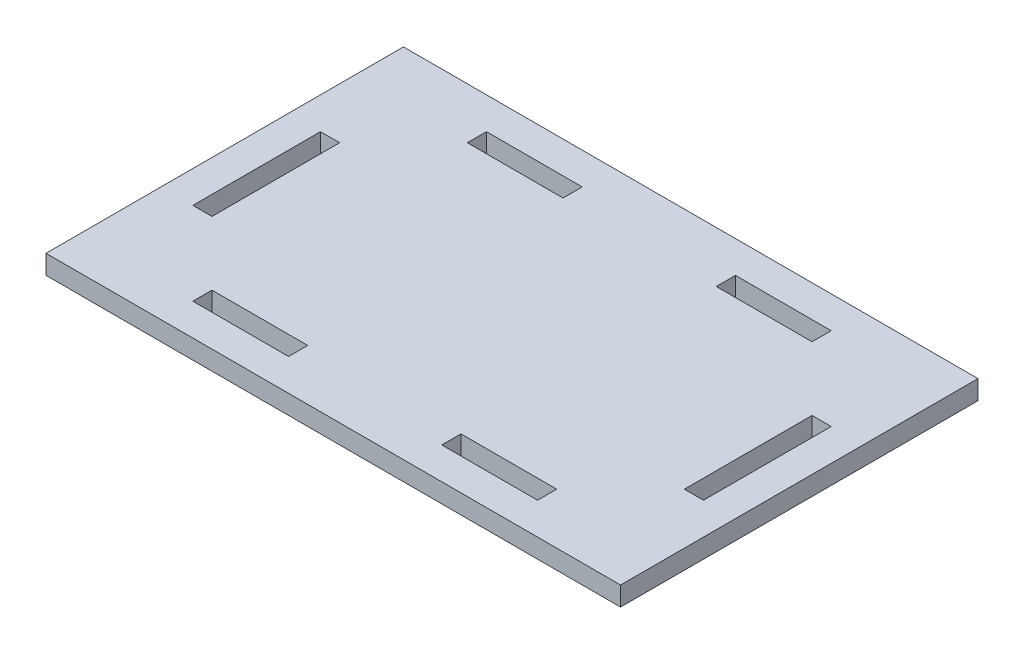
SolidWorks part; units mm, degrees
ref_plane "前视基准面" through (0, 0, 0) normal (0, 0, 1) x (1, 0, 0)
ref_plane "上视基准面" through (0, 0, 0) normal (0, 1, 0) x (1, 0, 0)
ref_plane "右视基准面" through (0, 0, 0) normal (1, 0, 0) x (0, 0, -1)
other "Configuration Table"
sketch "草图1" plane through (0, 0, 0) normal (0, 1, 0) x (1, 0, 0)
  line L0 (0, 12.4054) -> (0, -7.9459) construction
  line L1 (-45, 28) -> (45, 28)
  line L2 (-45, 28) -> (-45, -28)
  line L3 (-45, -28) -> (45, -28)
  line L4 (45, 28) -> (45, -28)
  line L5 (-45, 28) -> (45, -28) construction
  line L6 (-45, -28) -> (45, 28) construction
  line L7 (-40, 10) -> (-37, 10)
  line L8 (-40, 10) -> (-40, -10)
  line L9 (-40, -10) -> (-37, -10)
  line L10 (-37, 10) -> (-37, -10)
  line L11 (40, -10) -> (37, -10)
  line L12 (37, 10) -> (37, -10)
  line L13 (40, 10) -> (37, 10)
  line L14 (40, 10) -> (40, -10)
  line L15 (27, 20) -> (12, 20)
  line L16 (-27, 23) -> (-12, 23)
  line L17 (-27, 23) -> (-27, 20)
  line L18 (-27, 20) -> (-12, 20)
  line L19 (-12, 23) -> (-12, 20)
  line L20 (12, 23) -> (12, 20)
  line L21 (27, 23) -> (12, 23)
  line L22 (27, 23) -> (27, 20)
  line L23 (-10.6216, 0) -> (9.2432, 0) construction
  line L24 (27, -23) -> (27, -20)
  line L25 (27, -23) -> (12, -23)
  line L26 (12, -23) -> (12, -20)
  line L27 (27, -20) -> (12, -20)
  line L28 (-27, -20) -> (-12, -20)
  line L29 (-12, -23) -> (-12, -20)
  line L30 (-27, -23) -> (-12, -23)
  line L31 (-27, -23) -> (-27, -20)
  point P0 (0, 0)
  point P10 (-37, 0)
  dimension "D1" = 90
  dimension "D2" = 56
  dimension "D3" = 3
  dimension "D4" = 20
  dimension "D5" = 5
  dimension "D6" = 15
  dimension "D7" = 5
  dimension "D8" = 12
extrude "凸台-拉伸1" add sketch "草图1" along normal blind 3
